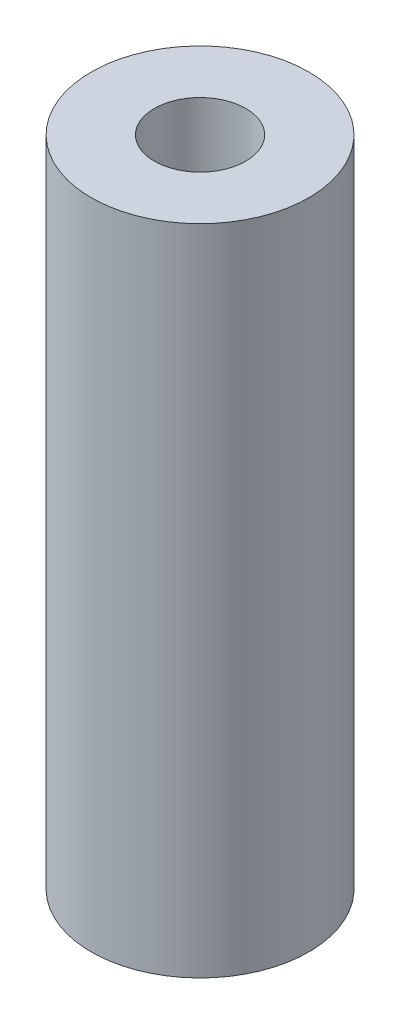
SolidWorks part; units mm, degrees
ref_plane "Front Plane" through (0, 0, 0) normal (0, 0, 1) x (1, 0, 0)
ref_plane "Top Plane" through (0, 0, 0) normal (0, 1, 0) x (1, 0, 0)
ref_plane "Right Plane" through (0, 0, 0) normal (1, 0, 0) x (0, 0, -1)
sketch "Sketch1" plane through (0, 0, 0) normal (0, 1, 0) x (1, 0, 0)
  circle A0 centre (0, 0) radius 2.667
  circle A1 centre (0, 0) radius 6.35
  dimension "D1" = 5.334
  dimension "D2" = 12.7
extrude "Boss-Extrude1" add sketch "Sketch1" along normal blind 38.1
